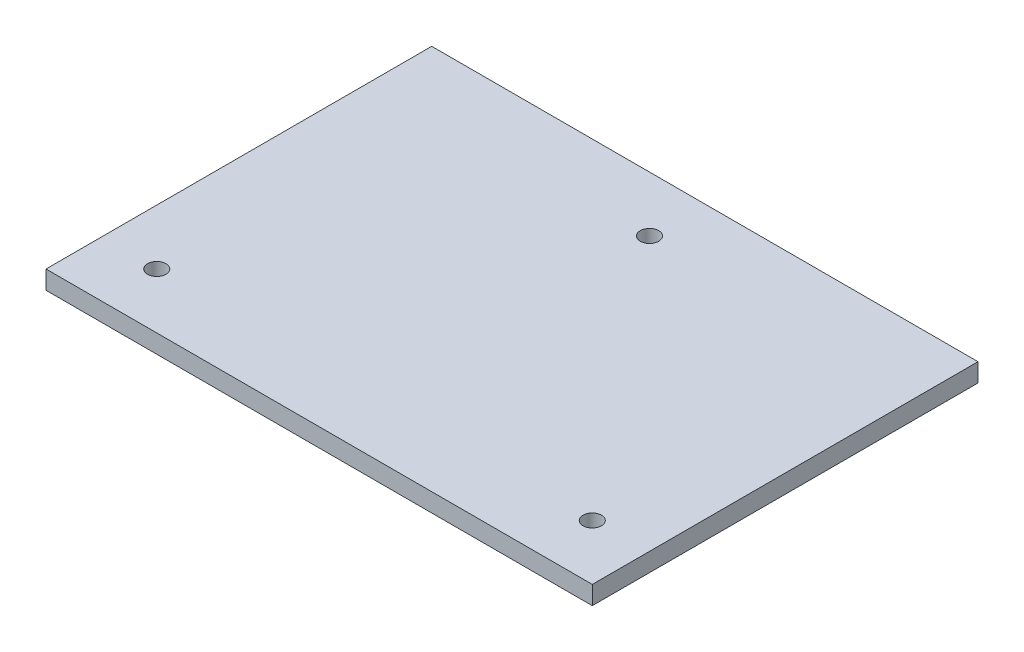
SolidWorks part; units mm, degrees
ref_plane "Front Plane" through (0, 0, 0) normal (0, 0, 1) x (1, 0, 0)
ref_plane "Top Plane" through (0, 0, 0) normal (0, 1, 0) x (1, 0, 0)
ref_plane "Right Plane" through (0, 0, 0) normal (1, 0, 0) x (0, 0, -1)
sketch "Sketch1" plane through (0, 0, 0) normal (0, 1, 0) x (1, 0, 0)
  line L1 (-148, -104.5) -> (148, -104.5)
  line L2 (-148, -104.5) -> (-148, 104.5)
  line L3 (-148, 104.5) -> (148, 104.5)
  line L4 (148, -104.5) -> (148, 104.5)
  line L5 (-148, -104.5) -> (148, 104.5) construction
  line L6 (-148, 104.5) -> (148, -104.5) construction
  point P0 (0, 0)
  dimension "D1" = 296
  dimension "D2" = 209
extrude "Extrude1" add sketch "Sketch1" along normal blind 10
sketch "Sketch2" plane through (0, 0, 0) normal (0, -1, 0) x (1, 0, 0)
  line L0 (0, -74.5) -> (0, 74.5) construction
  line L1 (-118, 74.5) -> (118, 74.5) construction
  line L2 (-148, -104.5) -> (-148, 104.5) construction
  line L3 (148, -104.5) -> (-148, -104.5) construction
  circle A0 centre (-118, 74.5) radius 5
  circle A1 centre (118, 74.5) radius 5
  circle A2 centre (0, -74.5) radius 5
  dimension "D3" = 10
  dimension "D1" = 30
  dimension "D2" = 30
extrude "Cut-Extrude1" cut sketch "Sketch2" against normal up to next
